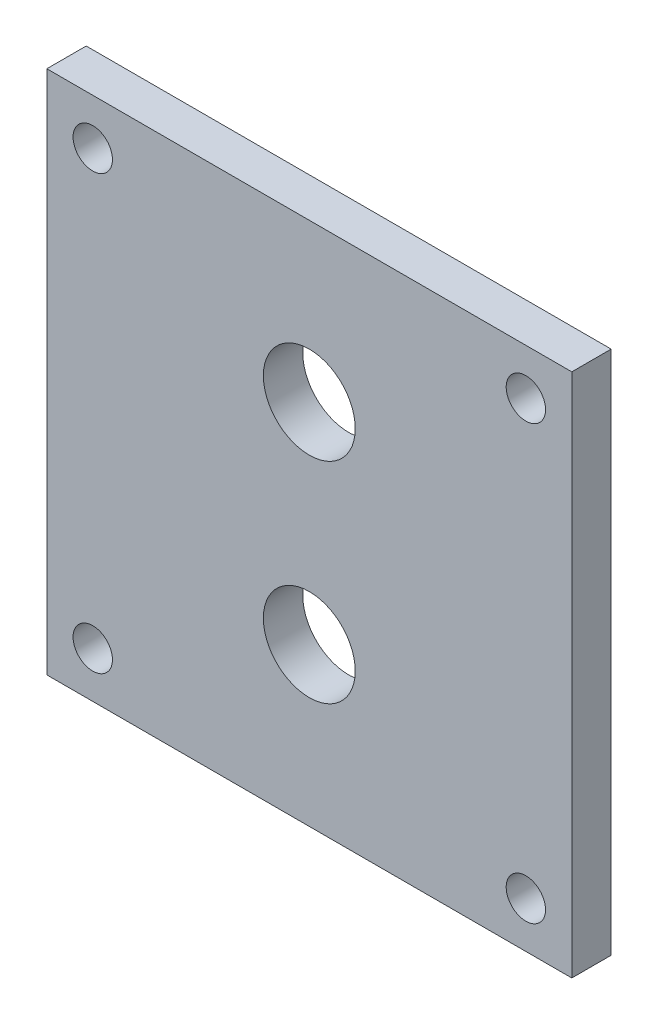
SolidWorks part; units mm, degrees
ref_plane "Front Plane" through (0, 0, 0) normal (0, 0, 1) x (1, 0, 0)
ref_plane "Top Plane" through (0, 0, 0) normal (0, 1, 0) x (1, 0, 0)
ref_plane "Right Plane" through (0, 0, 0) normal (1, 0, 0) x (0, 0, -1)
sketch "Sketch1" plane through (0, 0, 0) normal (0, 0, 1) x (1, 0, 0)
  line L1 (-63.5, 63.5) -> (63.5, 63.5)
  line L2 (-63.5, 63.5) -> (-63.5, -63.5)
  line L3 (-63.5, -63.5) -> (63.5, -63.5)
  line L4 (63.5, 63.5) -> (63.5, -63.5)
  line L5 (-63.5, 63.5) -> (63.5, -63.5) construction
  line L6 (-63.5, -63.5) -> (63.5, 63.5) construction
  point P0 (0, 0)
  dimension "D1" = 127
  dimension "D2" = 127
extrude "Boss-Extrude1" add sketch "Sketch1" along normal blind 9.525
sketch "Sketch2" plane through (0, 0, 0) normal (0, 0, -1) x (-1, 0, 0)
  line L4 (-63.5, 63.5) -> (63.5, 63.5) construction
  line L5 (63.5, -63.5) -> (-63.5, -63.5) construction
  line L6 (-63.5, -63.5) -> (-63.5, 63.5) construction
  circle A0 centre (0, 25.4) radius 11.1125
  circle A2 centre (0, -25.4) radius 11.1125
  dimension "D1" = 22.225
  dimension "D2" = 38.1
  dimension "D6" = 63.5
  dimension "D7" = 22.225
  dimension "D8" = 63.5
  dimension "D3" = 38.1
extrude "Cut-Extrude1" cut sketch "Sketch2" against normal up to surface (9.525 mm away) up to face at (0, 0, 9.525)
sketch "Sketch3" plane through (0, 0, 0) normal (0, 0, -1) x (-1, 0, 0)
  line L0 (-63.5, 63.5) -> (63.5, 63.5) construction
  line L1 (63.5, 63.5) -> (63.5, -63.5) construction
  line L2 (0, -63.5) -> (0, 63.5) construction
  line L3 (63.5, -63.5) -> (-63.5, -63.5) construction
  line L4 (63.5, 0) -> (-63.5, 0) construction
  line L5 (-63.5, -63.5) -> (-63.5, 63.5) construction
  circle A0 centre (52.3875, 52.3875) radius 4.7625
  circle A1 centre (52.3875, -52.3875) radius 4.7625
  circle A2 centre (-52.3875, 52.3875) radius 4.7625
  circle A3 centre (-52.3875, -52.3875) radius 4.7625
  dimension "D1" = 9.525
  dimension "D2" = 11.1125
  dimension "D3" = 11.1125
extrude "Cut-Extrude2" cut sketch "Sketch3" against normal up to surface (9.525 mm away) up to face at (11.1125, -25.4, 9.525)
